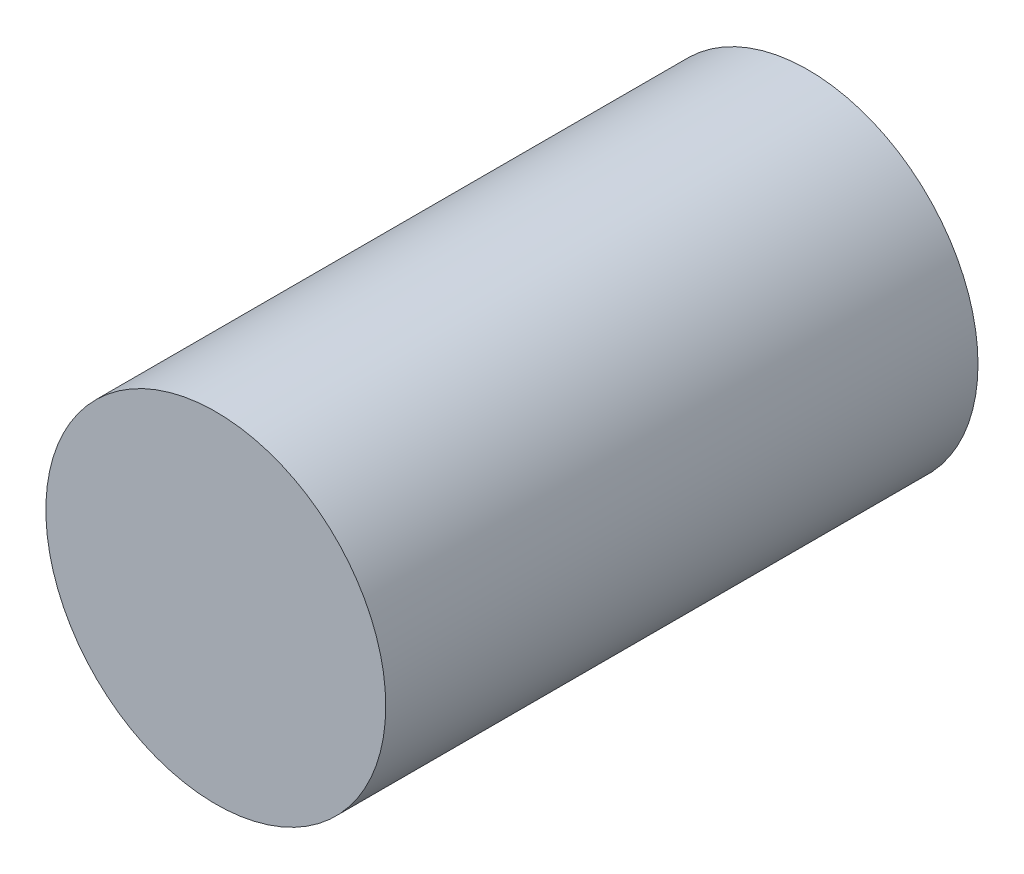
SolidWorks part; units mm, degrees
ref_plane "Piano frontale" through (0, 0, 0) normal (0, 0, 1) x (1, 0, 0)
ref_plane "Piano superiore" through (0, 0, 0) normal (0, 1, 0) x (1, 0, 0)
ref_plane "Piano destro" through (0, 0, 0) normal (1, 0, 0) x (0, 0, -1)
sketch "Schizzo1" plane through (0, 0, 0) normal (0, 0, 1) x (1, 0, 0)
  circle A0 centre (0, 0) radius 33
  dimension "D1" = 66
extrude "Estrusione-Estrusione1" add sketch "Schizzo1" along normal blind 115
